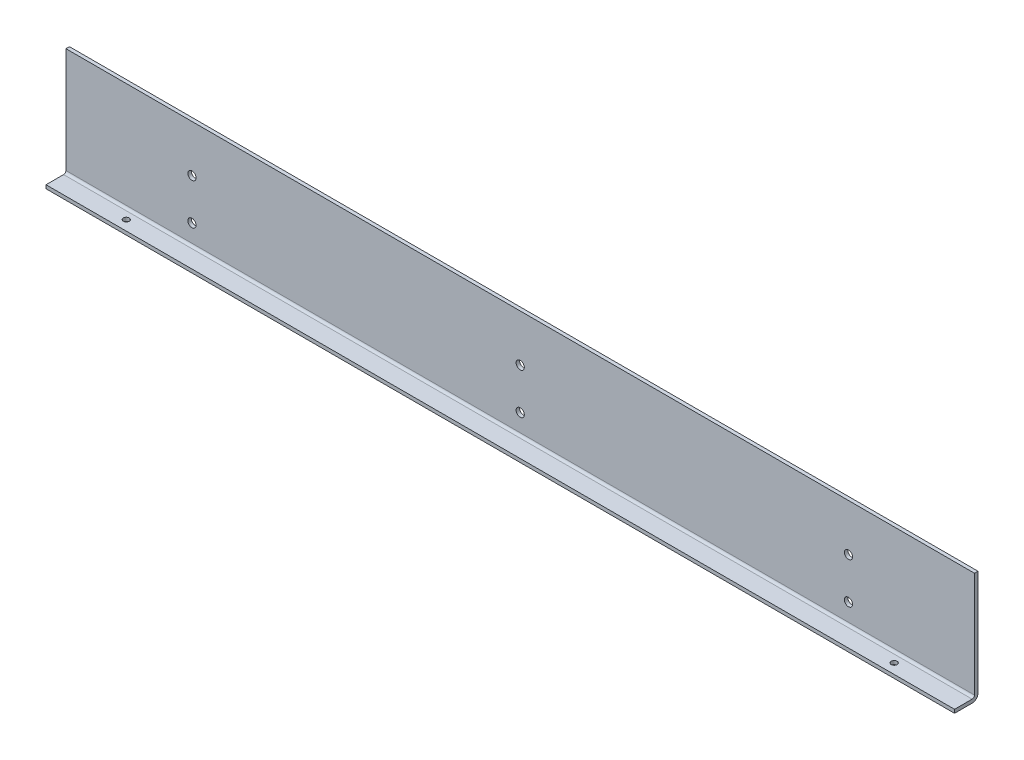
SolidWorks part; units mm, degrees
ref_plane "정면" through (0, 0, 0) normal (0, 0, 1) x (1, 0, 0)
ref_plane "윗면" through (0, 0, 0) normal (0, 1, 0) x (1, 0, 0)
ref_plane "우측면" through (0, 0, 0) normal (1, 0, 0) x (0, 0, -1)
sketch "스케치1" plane through (0, 0, 0) normal (0, 0, 1) x (1, 0, 0)
  line L1 (0, 0) -> (775, 0)
  line L2 (0, 0) -> (0, 95)
  line L3 (0, 95) -> (775, 95)
  line L4 (775, 0) -> (775, 95)
  dimension "D1" = 775
  dimension "D2" = 95
extrude "보스-돌출1" add sketch "스케치1" along normal blind 3
sketch "스케치2" plane through (0, 0, 3) normal (0, 0, 1) x (1, 0, 0)
  line L0 (775, 0) -> (775, 95) construction
  line L1 (0, 0) -> (775, 0)
  line L2 (0, 0) -> (0, 3)
  line L3 (0, 3) -> (775, 3)
  line L4 (775, 0) -> (775, 3)
  dimension "D1" = 3
extrude "보스-돌출2" add sketch "스케치2" along normal blind 17
sketch "스케치3" plane through (0, 0, 3) normal (0, 0, 1) x (1, 0, 0)
  line L0 (0, 0) -> (775, 0) construction
  line L1 (0, 95) -> (0, 3) construction
  circle A0 centre (107.5, 55) radius 3.5
  circle A1 centre (107.5, 20) radius 3.5
  circle A2 centre (387.5, 55) radius 3.5
  circle A3 centre (387.5, 20) radius 3.5
  circle A4 centre (667.5, 55) radius 3.5
  circle A5 centre (667.5, 20) radius 3.5
  point P12 (0, 0)
  point P13 (0, 0)
  point P14 (0, 0)
  point P15 (0, 0)
  point P16 (0, 0)
  point P17 (0, 0)
  dimension "D1" = 7
  dimension "D2" = 20
  dimension "D3" = 35
  dimension "D4" = 107.5
  dimension "D5" = 280
  dimension "D6" = 280
extrude "컷-돌출1" cut sketch "스케치3" against normal blind 17
sketch "스케치4" plane through (0, 3, 0) normal (0, 1, 0) x (1, 0, 0)
  line L0 (775, -20) -> (0, -20) construction
  line L1 (0, -20) -> (0, -3) construction
  circle A0 centre (60, -11.5) radius 2.5
  circle A1 centre (715, -11.5) radius 2.5
  point P6 (0, 0)
  dimension "D4" = 5
  dimension "D1" = 8.5
  dimension "D2" = 60
  dimension "D3" = 655
extrude "컷-돌출2" cut sketch "스케치4" against normal blind 17
fillet "필렛1" radius 5 1 edges at (387.5, 0, 0)
fillet "필렛2" radius 2 1 edges at (387.5, 3, 3)
